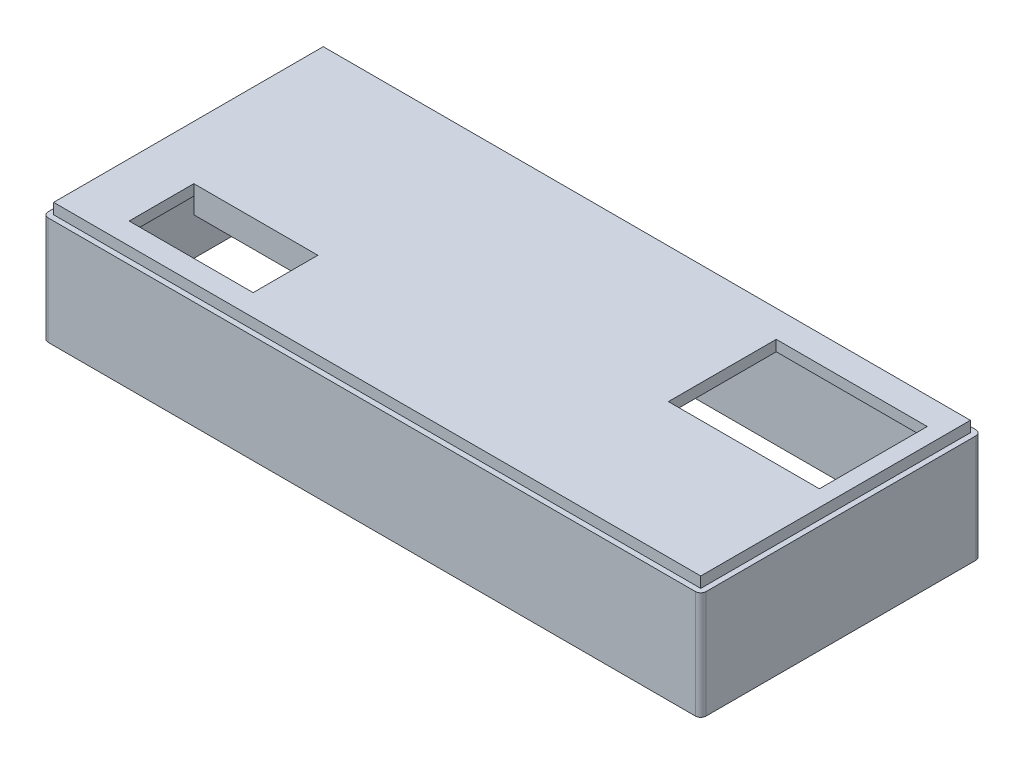
SolidWorks part; units mm, degrees
material "聚脂树脂"
ref_plane "前视基准面" through (0, 0, 0) normal (0, 0, 1) x (1, 0, 0)
ref_plane "上视基准面" through (0, 0, 0) normal (0, 1, 0) x (1, 0, 0)
ref_plane "右视基准面" through (0, 0, 0) normal (1, 0, 0) x (0, 0, -1)
other "Configuration Table"
sketch "草图1" plane through (0, 0, 0) normal (0, 1, 0) x (1, 0, 0)
  line L1 (0, 0) -> (120, 0)
  line L2 (0, 0) -> (0, -50)
  line L3 (0, -50) -> (120, -50)
  line L4 (120, 0) -> (120, -50)
  dimension "D1" = 120
  dimension "D2" = 50
extrude "凸台-拉伸1" add sketch "草图1" along normal blind 2
sketch "草图2" plane through (0, 0, 0) normal (0, -1, 0) x (1, 0, 0)
  line L4 (0, 50) -> (0, 0)
  line L5 (0, 0) -> (120, 0)
  line L6 (120, 0) -> (120, 50)
  line L7 (120, 50) -> (0, 50)
  line L8 (0, 50) -> (0, 0)
  line L9 (0, 0) -> (120, 0)
  line L10 (120, 0) -> (120, 50)
  line L11 (120, 50) -> (0, 50)
  line L12 (0, 50) -> (0, 0)
  line L13 (120, 50) -> (0, 50)
  line L14 (120, 0) -> (120, 50)
  line L15 (0, 0) -> (120, 0)
  line L16 (0, 50) -> (0, 0)
  line L17 (120, 50) -> (0, 50)
  line L18 (120, 0) -> (120, 50)
  line L19 (0, 0) -> (120, 0)
  dimension "D1" = 0
  dimension "D2" = 0
extrude "拉伸-薄壁2" add sketch "草图2" along normal blind 20 separate body thin contours L11 L8 L9 L10
sketch "草图3" plane through (0, 2, 0) normal (0, 1, 0) x (1, 0, 0)
  line L0 (120, 0) -> (0, 0) construction
  line L1 (89, -5) -> (117, -5)
  line L2 (89, -5) -> (89, -25)
  line L3 (89, -25) -> (117, -25)
  line L4 (117, -5) -> (117, -25)
  line L5 (120, -50) -> (120, 0) construction
  dimension "D1" = 5
  dimension "D2" = 3
  dimension "D3" = 28
  dimension "D4" = 20
extrude "切除-拉伸1" cut sketch "草图3" against normal up to next (2 mm away)
fillet "圆角2" radius 1 8 edges at (120, -10, 50) (121, -10, 51) (-1, -10, 51) (0, -10, 50) (0, -10, 0) (-1, -10, -1) (120, -10, 0) (121, -10, -1)
sketch "草图4" plane through (0, 0, 0) normal (0, -1, 0) x (1, 0, 0)
  line L4 (0, 50) -> (0, 0)
  line L5 (0, 0) -> (120, 0)
  line L6 (120, 0) -> (120, 50)
  line L7 (120, 50) -> (0, 50)
  line L8 (0, 50) -> (0, 0)
  line L9 (0, 0) -> (120, 0)
  line L10 (120, 0) -> (120, 50)
  line L11 (120, 50) -> (0, 50)
  dimension "D1" = 0
ref_plane "基准面1" through (-1, -50, 21) normal (0, 0, 1) x (1, 0, 0)
sketch "草图5" plane through (0, 0, 0) normal (0, -1, 0) x (1, 0, 0)
  line L4 (0, 50) -> (0, 0)
  line L5 (0, 0) -> (120, 0)
  line L6 (120, 0) -> (120, 50)
  line L7 (120, 50) -> (0, 50)
  line L8 (0, 50) -> (0, 0)
  line L9 (0, 0) -> (120, 0)
  line L10 (120, 0) -> (120, 50)
  line L11 (120, 50) -> (0, 50)
  line L16 (10, 33) -> (34, 33)
  line L17 (10, 34) -> (10, 33)
  line L18 (33, 34) -> (10, 34)
  line L19 (33, 46) -> (33, 34)
  line L20 (10, 46) -> (33, 46)
  line L21 (10, 47) -> (10, 46)
  line L22 (34, 47) -> (10, 47)
  line L23 (34, 33) -> (34, 47)
  line L24 (10, 33) -> (34, 33)
  line L25 (10, 34) -> (10, 33)
  line L26 (33, 34) -> (10, 34)
  line L27 (33, 46) -> (33, 34)
  line L28 (10, 46) -> (33, 46)
  line L29 (10, 47) -> (10, 46)
  line L30 (34, 47) -> (10, 47)
  line L31 (34, 33) -> (34, 47)
  dimension "D1" = 0
  dimension "D2" = 0
extrude "凸台-拉伸2" add sketch "草图5" along normal blind 3 contours L24 L31 L30 L29 L28 L27 L26 L25
sketch "草图6" plane through (0, 0, 0) normal (0, -1, 0) x (1, 0, 0)
  line L1 (10, 46) -> (33, 46)
  line L2 (10, 46) -> (10, 34)
  line L3 (10, 34) -> (33, 34)
  line L4 (33, 46) -> (33, 34)
extrude "切除-拉伸2" cut sketch "草图6" against normal up to next (2 mm away)
